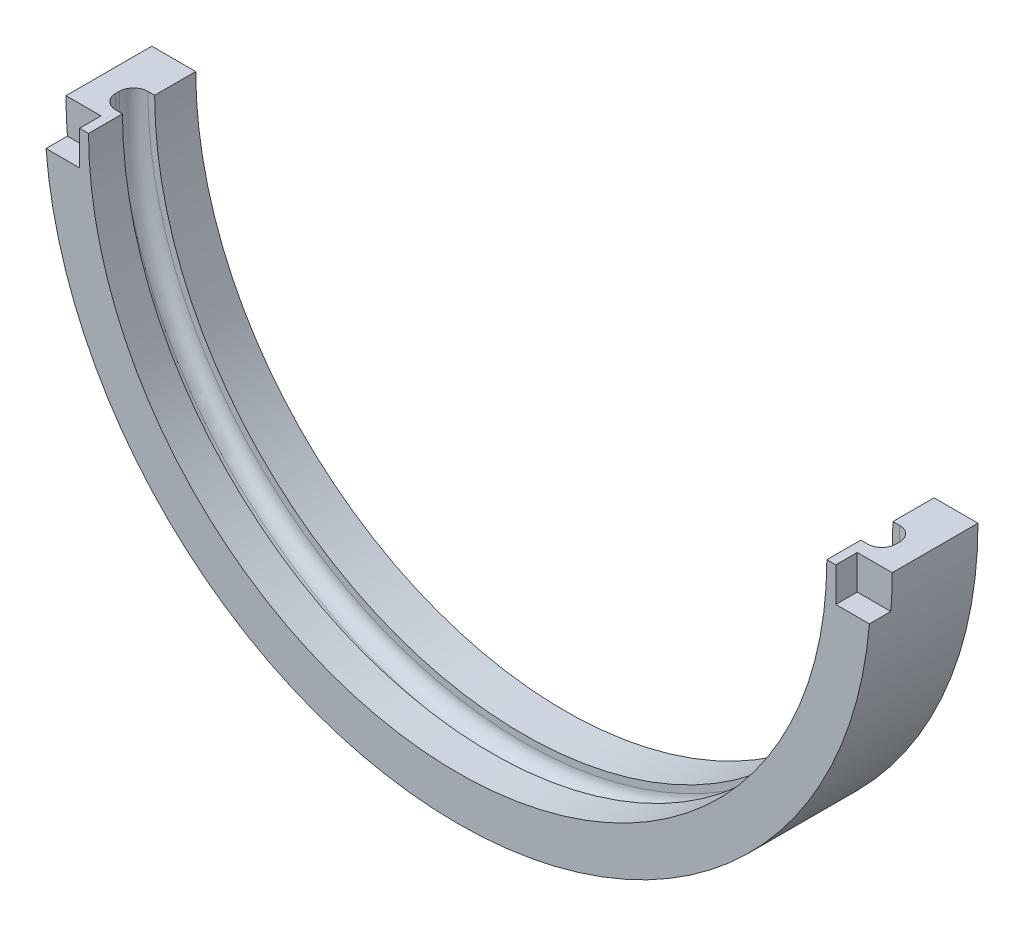
SolidWorks part; units mm, degrees
material "ABS"
ref_plane "Front Plane" through (0, 0, 0) normal (0, 0, 1) x (1, 0, 0)
ref_plane "Top Plane" through (0, 0, 0) normal (0, 1, 0) x (1, 0, 0)
ref_plane "Right Plane" through (0, 0, 0) normal (1, 0, 0) x (0, 0, -1)
sketch "Sketch1" plane through (0, 0, 0) normal (0, 0, 1) x (1, 0, 0)
  line L0 (-69.342, 73.406) -> (-73.406, 73.406)
  line L1 (69.342, 73.406) -> (73.406, 73.406)
  circle A0 centre (0, 73.406) radius 73.406
  circle A1 centre (0, 73.406) radius 69.342
  dimension "D1" = 146.812
  dimension "D2" = 138.684
extrude "Boss-Extrude1" add sketch "Sketch1" along normal blind 5.715 contours A1 L0 A0 L1
sketch "Sketch3" plane through (0, 0, 5.715) normal (0, 0, 1) x (1, 0, 0)
  line L0 (-65.5955, 73.406) -> (-73.406, 73.406)
  line L1 (65.5955, 73.406) -> (73.406, 73.406)
  circle A0 centre (0, 73.406) radius 73.406
  circle A1 centre (0, 73.406) radius 65.5955
  arc M3 (69.342, 73.406) -> (-69.342, 73.406) centre (0, 73.406) cw
  line M4 (-69.342, 73.406) -> (-73.406, 73.406)
  arc M5 (-73.406, 73.406) -> (73.406, 73.406) centre (0, 73.406) ccw
  line M6 (73.406, 73.406) -> (69.342, 73.406)
  dimension "D1" = 131.191
extrude "Boss-Extrude2" add sketch "Sketch3" along normal blind 6.0325 contours A1 L0 L1 M3 | M6 M3 M4 M5
sketch "Sketch4" plane through (0, 0, 0) normal (0, 0, -1) x (-1, 0, 0)
  line L0 (-65.5955, 73.406) -> (-73.406, 73.406)
  line L1 (65.5955, 73.406) -> (73.406, 73.406)
  circle A0 centre (0, 73.406) radius 73.406
  circle A1 centre (0, 73.406) radius 65.5955
  arc M3 (69.342, 73.406) -> (-69.342, 73.406) centre (0, 73.406) cw
  line M4 (-69.342, 73.406) -> (-73.406, 73.406)
  arc M5 (-73.406, 73.406) -> (73.406, 73.406) centre (0, 73.406) ccw
  line M6 (73.406, 73.406) -> (69.342, 73.406)
extrude "Boss-Extrude3" add sketch "Sketch4" along normal blind 7.3025 contours A1 L0 L1 M3 | M6 M3 M4 M5
fillet "Fillet1" radius 2.54 2 edges at (0, 4.064, 5.715) (0, 4.064, 0)
sketch "Sketch5" plane through (0, 0, 0) normal (0, 1, 0) x (1, 0, 0)
  line L0 (64.2819, -2.8575) -> (-64.2819, -2.8575) construction
  circle A0 centre (0, -2.8575) radius 1.524
  dimension "D1" = 3.048
extrude "Cut-Extrude1" [suppressed] cut sketch "Sketch5" along normal blind 6.35
sketch "Sketch6" plane through (0, 0, 11.7475) normal (0, 0, 1) x (1, 0, 0)
  line L0 (-65.5955, 73.406) -> (-73.406, 73.406) construction
  line L1 (-67.1839, 73.406) -> (-73.8294, 73.406)
  line L2 (-67.1839, 73.406) -> (-67.1839, 67.31)
  line L3 (-67.1839, 67.31) -> (-73.8294, 67.31)
  line L4 (-73.8294, 73.406) -> (-73.8294, 67.31)
  line L5 (0, 10.7538) -> (0, 95.14) construction
  line L18 (67.1839, 67.31) -> (73.8294, 67.31)
  line L19 (73.8294, 73.406) -> (73.8294, 67.31)
  line L20 (67.1839, 73.406) -> (73.8294, 73.406)
  line L21 (67.1839, 73.406) -> (67.1839, 67.31)
  dimension "D1" = 6.096
extrude "Cut-Extrude5" cut sketch "Sketch6" against normal blind 3.81
